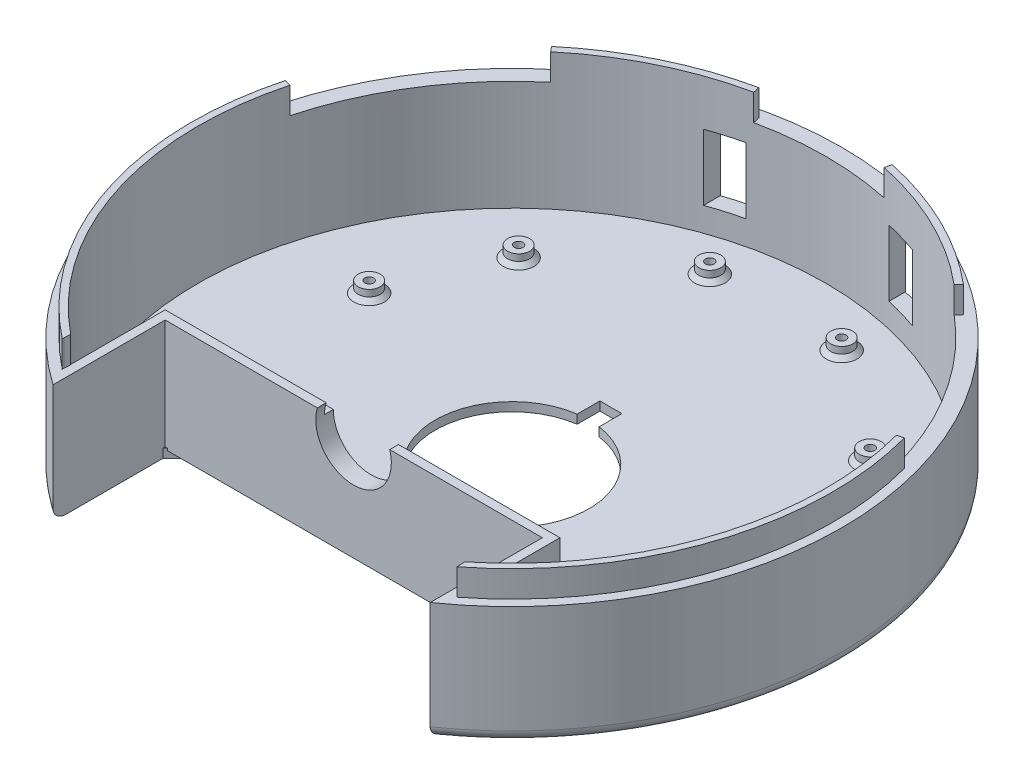
SolidWorks part; units mm, degrees
ref_plane "정면" through (0, 0, 0) normal (0, 0, 1) x (1, 0, 0)
ref_plane "윗면" through (0, 0, 0) normal (0, 1, 0) x (1, 0, 0)
ref_plane "우측면" through (0, 0, 0) normal (1, 0, 0) x (0, 0, -1)
sketch "스케치1" plane through (0, 0, 0) normal (0, 1, 0) x (1, 0, 0)
  line L0 (-135.6859, 0) -> (157.1571, 0) construction
  line L1 (0, 101.5408) -> (0, -87.2266) construction
  circle A0 centre (0, 0) radius 150
  dimension "D1" = 300
extrude "보스-돌출1" add sketch "스케치1" along normal blind 4
sketch "스케치2" plane through (0, 4, 0) normal (0, 1, 0) x (1, 0, 0)
  line L0 (-169.9346, 0) -> (189.9475, 0) construction
  line L1 (0, 157.4704) -> (0, -173.2701) construction
  circle A0 centre (0, 0) radius 145.8
  circle A1 centre (0, 0) radius 150
  circle A2 centre (0, 0) radius 150
  dimension "D1" = 0
  dimension "D2" = 4.2
extrude "보스-돌출2" add sketch "스케치2" along normal blind 50
sketch "스케치3" plane through (0, 4, 0) normal (0, 1, 0) x (1, 0, 0)
  circle A0 centre (0, 0) radius 142.8
  circle A1 centre (0, 0) radius 145.8
  circle A2 centre (0, 0) radius 145.8
  dimension "D1" = 0
  dimension "D2" = 3
extrude "보스-돌출3" add sketch "스케치3" along normal blind 62
sketch "스케치4" plane through (0, 0, 0) normal (0, -1, 0) x (1, 0, 0)
  line L5 (85.8, 73) -> (85.8, 123.038)
  line L6 (84.8, 72) -> (85.8, 73)
  line L7 (-84.8, 72) -> (84.8, 72)
  line L8 (-85.8, 73) -> (-84.8, 72)
  line L9 (-85.8, 123.038) -> (-85.8, 73)
  line L10 (85.8, 73) -> (85.8, 123.038)
  line L11 (84.8, 72) -> (85.8, 73)
  line L12 (-84.8, 72) -> (84.8, 72)
  line L13 (-85.8, 73) -> (-84.8, 72)
  line L14 (-85.8, 123.038) -> (-85.8, 73)
  arc A1 (85.8, 123.038) -> (-85.8, 123.038) centre (0, 0) ccw
  arc A2 (85.8, 123.038) -> (-85.8, 123.038) centre (0, 0) ccw
  dimension "D1" = 0
extrude "컷-돌출1" cut sketch "스케치4" against normal through all both and the other way through all contours L12 L11 L10 A2 L14 L13
sketch "스케치5" plane through (0, 4, 0) normal (0, 1, 0) x (1, 0, 0)
  line L31 (-89.8, -71.3431) -> (-89.8, -114.1499)
  line L32 (-86.4569, -68) -> (-89.8, -71.3431)
  line L33 (84.8, -68) -> (-86.4569, -68)
  line L34 (-89.8, -71.3431) -> (-89.8, -114.1499)
  line L35 (85.8, -73) -> (85.8, -123.038) construction
  line L36 (84.8, -68) -> (-86.4569, -68)
  line L39 (89.8, -71.3431) -> (89.8, -68)
  line L40 (89.8, -68) -> (86.4569, -68)
  line L41 (-86.4569, -68) -> (-89.8, -68)
  line L42 (86.4569, -68) -> (-84.8, -68)
  line L43 (89.8, -114.1499) -> (89.8, -71.3431)
  line L44 (89.8, -71.3431) -> (86.4569, -68)
  line L45 (86.4569, -68) -> (-84.8, -68)
  line L46 (89.8, -114.1499) -> (89.8, -71.3431)
  line L47 (-89.8, -68) -> (-89.8, -71.3431)
  line L48 (-85.8, -72) -> (85.8, -72)
  line L49 (-85.8, -72) -> (-85.8, -117.8813)
  line L51 (85.8, -72) -> (85.8, -117.8813)
  line L52 (84.8, -72) -> (-84.8, -72) construction
  line L53 (-85.8, -73) -> (-85.8, -123.038) construction
  line L54 (-89.8, -114.1499) -> (-89.8, -114.8634)
  line L55 (89.8, -114.1499) -> (89.8, -114.8634)
  arc A0 (-85.8, -117.8813) -> (-89.8, -114.8634) centre (0, 0) cw
  arc A1 (85.8, -117.8813) -> (-85.8, -117.8813) centre (0, 0) ccw construction
  arc A2 (89.8, -114.8634) -> (85.8, -117.8813) centre (0, 0) cw
  line M11 (-85.8, -114.1499) -> (-85.8, -73)
  line M13 (-84.8, -72) -> (84.8, -72)
  line M15 (85.8, -73) -> (85.8, -114.1499)
  arc M16 (85.8, -114.1499) -> (-85.8, -114.1499) centre (0, 0) ccw
  dimension "D1" = 4
  dimension "D2" = 4
extrude "보스-돌출4" add sketch "스케치5" along normal blind 50 contours L48 L51 L46 L39 L40 L45 L36 L41 L47 L34 L49 M15 M16 M11 M13
sketch "스케치6" plane through (0, 66, 0) normal (0, 1, 0) x (1, 0, 0)
  line L1 (-89.8, -114.1499) -> (-89.6744, -111.1321)
  line L2 (-89.8, -117.8813) -> (-89.8, -114.1499)
  line L3 (-89.8, -114.8634) -> (-89.8, -114.1499)
  line L4 (-85.8, -117.8813) -> (-85.8, -114.1499) construction
  line L5 (-85.8, -117.8813) -> (-85.8, -114.1499)
  arc A2 (85.8, -117.8813) -> (-85.8, -117.8813) centre (0, 0) ccw construction
  arc A3 (-89.8, -114.8634) -> (-85.8, -117.8813) centre (0, 0) ccw
  arc A4 (85.8, -114.1499) -> (-85.8, -114.1499) centre (0, 0) ccw construction
  arc A5 (-89.6744, -111.1321) -> (-85.8, -114.1499) centre (0, 0) ccw
  dimension "D2" = 4
  dimension "D1" = 4
extrude "컷-돌출2" cut sketch "스케치6" against normal blind 12
mirror "대칭 복사1" about plane through (0, 0, 0) normal (1, 0, 0) of "컷-돌출2"
fillet "필렛1" radius 5 1 edges
sketch "스케치7" plane through (0, 0, 0) normal (0, -1, 0) x (1, 0, 0)
  circle A0 centre (0, 0) radius 35
  dimension "D1" = 70
extrude "컷-돌출3" cut sketch "스케치7" against normal through all both and the other way through all
sketch "스케치8" plane through (0, 54, 0) normal (0, 1, 0) x (1, 0, 0)
  line L0 (0, -51.6737) -> (0, 51.2938) construction
  line L1 (-65.732, 0) -> (212.7742, 0) construction
  line L2 (0, 0) -> (-168.2564, 45.0842) construction
  line L3 (-31.1868, 146.7221) -> (-29.5235, 138.897)
  line L4 (0, 142) -> (0, 150)
  line L5 (0, 0) -> (-144.9394, 172.7321) construction
  line L7 (-140.0592, 37.5288) -> (-144.8889, 38.8229)
  line L8 (-93.2042, 111.0764) -> (-96.4181, 114.9067)
  line L9 (-136.1955, 36.4935) -> (-140.0592, 37.5288)
  line L10 (-90.6331, 108.0123) -> (-93.2042, 111.0764)
  line L11 (0, 0) -> (-38.5222, 181.2329) construction
  circle A0 centre (0, 0) radius 145 construction
  circle A2 centre (0, 0) radius 150 construction
  arc A3 (-96.4181, 114.9067) -> (-144.8889, 38.8229) centre (0, 0) ccw
  arc A4 (-90.6331, 108.0123) -> (-136.1955, 36.4935) centre (0, 0) ccw
  arc A6 (0, 150) -> (-31.1868, 146.7221) centre (0, 0) ccw
  arc A7 (0, 142) -> (-29.5235, 138.897) centre (0, 0) ccw
  arc M14 (-89.8, -114.8634) -> (89.8, -114.8634) centre (0, 0) cw
  arc M19 (85.8, -123.038) -> (-85.8, -123.038) centre (0, 0) ccw
  dimension "D4" = 8
  dimension "D1" = 15
  dimension "D2" = 40
  dimension "D3" = 12
extrude "컷-돌출4" cut sketch "스케치8" along normal blind 25 contours L4 L3 M14 M19 | A7 L4 L3 M14 | A4 L9 L7 A3 L8 L10
mirror "대칭 복사2" about plane through (0, 0, 0) normal (1, 0, 0) of "컷-돌출4"
sketch "스케치9" plane through (0, 0, 0) normal (0, -1, 0) x (1, 0, 0)
  line L0 (0, -17.3985) -> (0, 32.5371) construction
  line L2 (5, -25) -> (-5, -25)
  line L3 (5, -25) -> (5, -45)
  line L4 (5, -45) -> (-5, -45)
  line L5 (-5, -25) -> (-5, -45)
  line L6 (5, -25) -> (-5, -45) construction
  line L7 (5, -45) -> (-5, -25) construction
  circle A0 centre (0, 0) radius 35 construction
  point P1 (0, -35)
  dimension "D1" = 20
  dimension "D2" = 10
extrude "컷-돌출5" cut sketch "스케치9" against normal blind 25
sketch "스케치10" plane through (0, 0, 68) normal (0, 0, -1) x (-1, 0, 0)
  circle A0 centre (0.1171, 49) radius 17.2
  ellipse E0 centre (0.1171, 49) end of major axis (0.1171, 66.2) minor radius 17.2 (16.5743, 54) -> (-16.3401, 54) ccw construction
extrude "컷-돌출6" cut sketch "스케치10" against normal blind 25
sketch "스케치11" plane through (0, 0, 68) normal (0, 0, -1) x (-1, 0, 0)
  line L0 (17.3171, 49) -> (21.3171, 49)
  line L1 (-17.0829, 49) -> (-21.0829, 49)
  arc A1 (-16.3401, 54) -> (16.5743, 54) centre (0.1171, 49) ccw construction
  arc A2 (-20.1674, 55.1628) -> (20.4016, 55.1628) centre (0.1171, 49) ccw
  arc A3 (-21.0829, 49) -> (21.3171, 49) centre (0.1171, 49) ccw
  arc A4 (-17.0829, 49) -> (17.3171, 49) centre (0.1171, 49) ccw
  dimension "D1" = 4
extrude "보스-돌출5" add sketch "스케치11" along normal blind 4
sketch "스케치12" plane through (0, 4, 0) normal (0, 1, 0) x (1, 0, 0)
  circle A110 centre (100, 35) radius 2 construction
  circle A111 centre (100, 35) radius 2
  circle A112 centre (100, 35) radius 5
  circle A117 centre (-80, 83) radius 2 construction
  circle A118 centre (-100, 35) radius 5 construction
  circle A119 centre (-100, 35) radius 2 construction
  circle A122 centre (-30, 120) radius 2 construction
  circle A123 centre (30, 120) radius 2 construction
  circle A124 centre (80, 83) radius 2 construction
  circle A125 centre (-80, 83) radius 2
  circle A126 centre (-100, 35) radius 5
  circle A127 centre (-100, 35) radius 2
  circle A130 centre (-30, 120) radius 2
  circle A131 centre (30, 120) radius 2
  circle A132 centre (80, 83) radius 2
  circle A135 centre (-80, 83) radius 5
  circle A136 centre (-30, 120) radius 5
  circle A137 centre (30, 120) radius 5
  circle A138 centre (80, 83) radius 5
  dimension "D1" = 3
  dimension "D4" = 3
  dimension "D5" = 3
  dimension "D6" = 3
  dimension "D7" = 3
extrude "보스-돌출6" add sketch "스케치12" along normal blind 5
chamfer "모따기1" distance 2 angle 45 6 edges at (30, 4, -115) (80, 4, -78) (100, 4, -30) (-100, 4, -30) (-80, 4, -78) (-30, 4, -115)
chamfer "모따기2" distance 3 angle 45 1 edges at (0, 0, 72)
sketch "스케치13" plane through (0, 0, 0) normal (0, 0, 1) x (1, 0, 0)
  line L0 (0, 109.3409) -> (0, -50.5893) construction
  line L1 (-145, 0) -> (145, 0) construction
  line L2 (-47.5, 15) -> (-32.5, 15)
  line L3 (-47.5, 15) -> (-47.5, 45)
  line L4 (-47.5, 45) -> (-32.5, 45)
  line L5 (-32.5, 15) -> (-32.5, 45)
  line L6 (-47.5, 15) -> (-32.5, 45) construction
  line L7 (-47.5, 45) -> (-32.5, 15) construction
  line L8 (47.5, 45) -> (32.5, 15) construction
  line L9 (47.5, 15) -> (32.5, 45) construction
  line L10 (32.5, 15) -> (32.5, 45)
  line L11 (47.5, 45) -> (32.5, 45)
  line L12 (47.5, 15) -> (47.5, 45)
  line L13 (47.5, 15) -> (32.5, 15)
  point P3 (-40, 30)
  point P14 (40, 30)
  dimension "D1" = 40
  dimension "D2" = 30
  dimension "D3" = 15
  dimension "D4" = 30
extrude "컷-돌출7" cut sketch "스케치13" against normal through all
